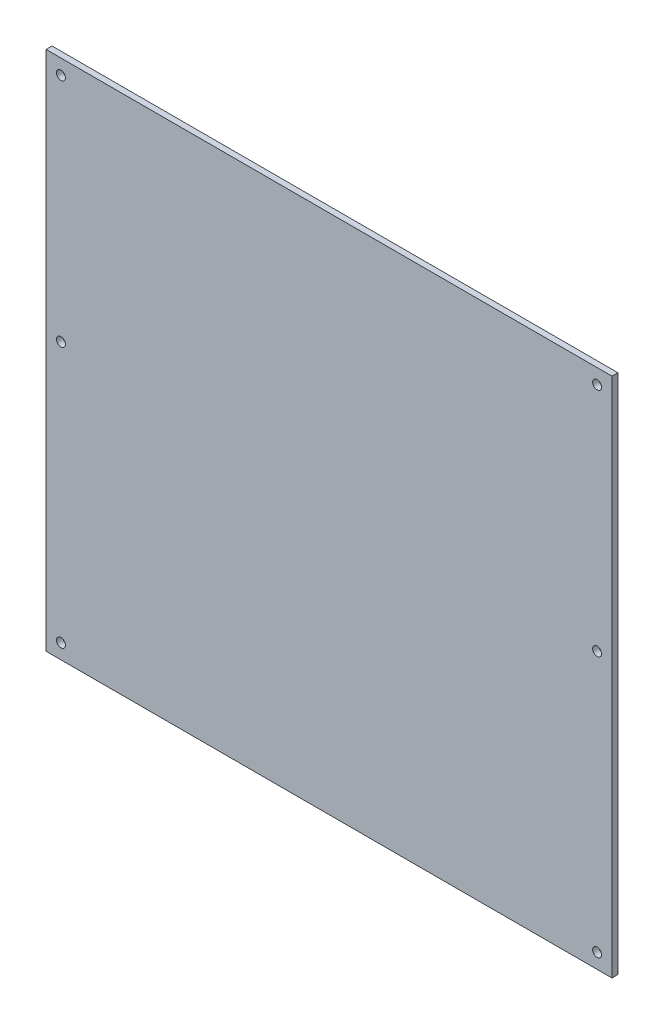
SolidWorks part; units mm, degrees
material "Sklo"
ref_plane "Přední rovina" through (0, 0, 0) normal (0, 0, 1) x (1, 0, 0)
ref_plane "Horní rovina" through (0, 0, 0) normal (0, 1, 0) x (1, 0, 0)
ref_plane "Pravá rovina" through (0, 0, 0) normal (1, 0, 0) x (0, 0, -1)
sketch "Skica1" plane through (0, 0, 0) normal (0, 0, 1) x (1, 0, 0)
  line L1 (190, -175) -> (-190, -175)
  line L2 (190, -175) -> (190, 175)
  line L3 (190, 175) -> (-190, 175)
  line L4 (-190, -175) -> (-190, 175)
  line L5 (190, -175) -> (-190, 175) construction
  line L6 (190, 175) -> (-190, -175) construction
  circle A0 centre (-180, 165) radius 3
  circle A1 centre (180, 165) radius 3
  circle A2 centre (180, 10) radius 3
  circle A3 centre (180, -165) radius 3
  circle A4 centre (-180, 10) radius 3
  circle A5 centre (-180, -165) radius 3
  point P0 (0, 0)
  dimension "D3" = 6
  dimension "D1" = 380
  dimension "D2" = 350
  dimension "D4" = 10
  dimension "D5" = 10
  dimension "D6" = 10
  dimension "D7" = 10
  dimension "D8" = 10
extrude "Přidat vysunutím1" add sketch "Skica1" along normal blind 4
